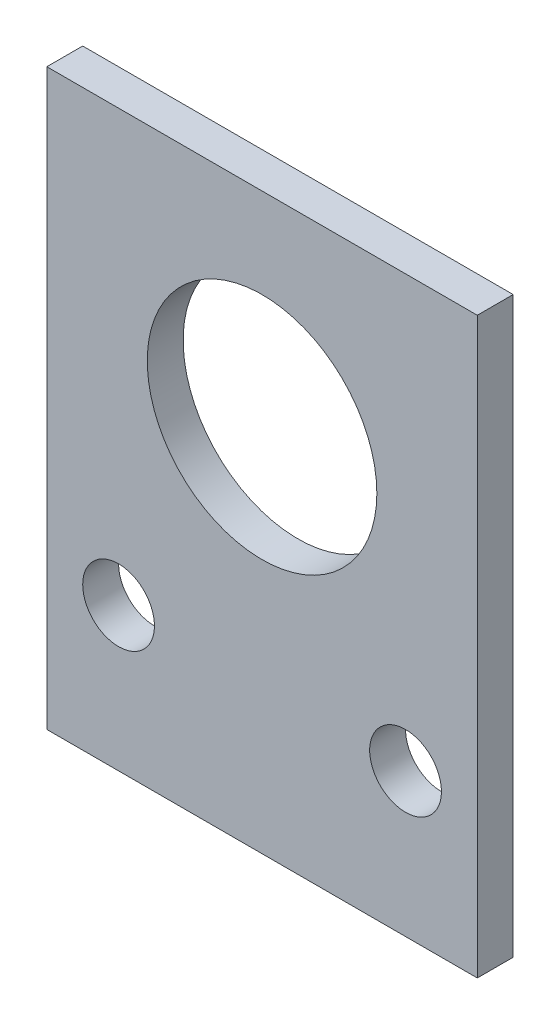
SolidWorks part; units mm, degrees
ref_plane "Front Plane" through (0, 0, 0) normal (0, 0, 1) x (1, 0, 0)
ref_plane "Top Plane" through (0, 0, 0) normal (0, 1, 0) x (1, 0, 0)
ref_plane "Right Plane" through (0, 0, 0) normal (1, 0, 0) x (0, 0, -1)
other "Center of Mass"
sketch "Sketch1" plane through (0, 0, 0) normal (0, 0, 1) x (1, 0, 0)
  line L0 (-30, -20) -> (30, -20) construction
  line L1 (-30, 40) -> (30, 40)
  line L2 (-30, 40) -> (-30, -40)
  line L3 (-30, -40) -> (30, -40)
  line L4 (30, 40) -> (30, -40)
  line L5 (-14.1814, 18.9086) -> (30, -40) construction
  line L6 (-30, -40) -> (14.1814, 18.9086) construction
  line L7 (0, 11.5) -> (0, -47.6893) construction
  line L8 (0, 11.5) -> (0, 33.5) construction
  circle A0 centre (0, 11.5) radius 16
  circle A1 centre (20, -20) radius 5
  circle A7 centre (-20, -20) radius 5
  point P0 (0, 0)
  dimension "D4" = 32
  dimension "D6" = 10
  dimension "D7" = 22
  dimension "D1" = 80
  dimension "D2" = 60
  dimension "D3" = 20
  dimension "D5" = 51.5
  dimension "D10" = 20
extrude "Boss-Extrude1" add sketch "Sketch1" along normal blind 5
